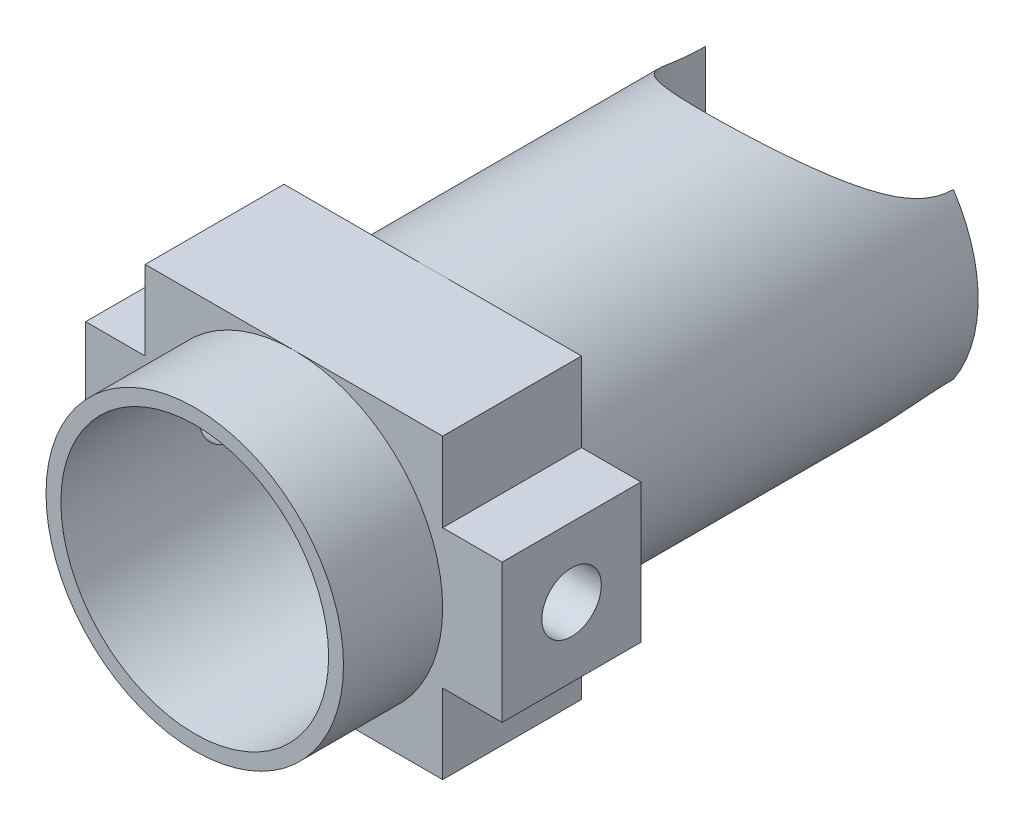
SolidWorks part; units mm, degrees
ref_plane "Спереди" through (0, 0, 0) normal (0, 0, 1) x (1, 0, 0)
ref_plane "Сверху" through (0, 0, 0) normal (0, 1, 0) x (1, 0, 0)
ref_plane "Справа" through (0, 0, 0) normal (1, 0, 0) x (0, 0, -1)
sketch "Эскиз1" plane through (0, 0, 0) normal (0, 0, 1) x (1, 0, 0)
  line L0 (0, 30) -> (0, 22)
  line L1 (0, 30) -> (30, 30)
  line L2 (30, 30) -> (30, 22)
  line L3 (30, 0) -> (0, 0)
  line L4 (30, 22) -> (36, 22)
  line L5 (30, 15) -> (30, 22) construction
  line L6 (30, 15) -> (30, 8) construction
  line L7 (36, 22) -> (36, 8)
  line L8 (36, 8) -> (30, 8)
  line L9 (30, 0) -> (30, 8)
  line L10 (0, 22) -> (-6, 22)
  line L11 (-6, 22) -> (-6, 8)
  line L12 (-6, 8) -> (0, 8)
  line L13 (0, 8) -> (0, 0)
  circle A0 centre (15, 15) radius 13.5
  dimension "D3" = 27
  dimension "D1" = 30
  dimension "D2" = 30
  dimension "D4" = 7
  dimension "D5" = 6
  dimension "D6" = 8
extrude "Бобышка-Вытянуть1" add sketch "Эскиз1" along normal blind 14
sketch "Эскиз2" plane through (0, 0, 14) normal (0, 0, 1) x (1, 0, 0)
  circle A0 centre (15, 15) radius 13.5
  circle A1 centre (15, 15) radius 15
extrude "Бобышка-Вытянуть2" add sketch "Эскиз2" along normal blind 10
sketch "Эскиз3" plane through (0, 0, 0) normal (0, 0, -1) x (-1, 0, 0)
  circle A0 centre (-15, 15) radius 15
extrude "Бобышка-Вытянуть3" add sketch "Эскиз3" along normal blind 40
sketch "Эскиз4" plane through (0, 0, -40) normal (0, 0, -1) x (-1, 0, 0)
  circle A0 centre (-15, 15) radius 10
  dimension "D1" = 20
extrude "Вырез-Вытянуть1" cut sketch "Эскиз4" against normal blind 40
loft "Вырез-По сечениям1" cut section edge at (5, 15, -40) section edge at (28.5, 15, 0)
sketch "Эскиз5" plane through (0, 0, -40) normal (0, 0, -1) x (-1, 0, 0)
  circle A0 centre (-15, 15) radius 13
  dimension "D1" = 26
sketch "Эскиз6" plane through (36, 0, 0) normal (1, 0, 0) x (0, 0, -1)
  circle A0 centre (-7, 15) radius 3
  dimension "D1" = 6
extrude "Вырез-Вытянуть2" cut sketch "Эскиз6" against normal through all
sketch "Эскиз7" plane through (0, 30, 0) normal (0, 1, 0) x (1, 0, 0)
  line L0 (28, 40) -> (2, 40) construction
  circle A0 centre (15, 40) radius 12.5
  dimension "D1" = 25
extrude "Вырез-Вытянуть3" cut sketch "Эскиз7" against normal through all
